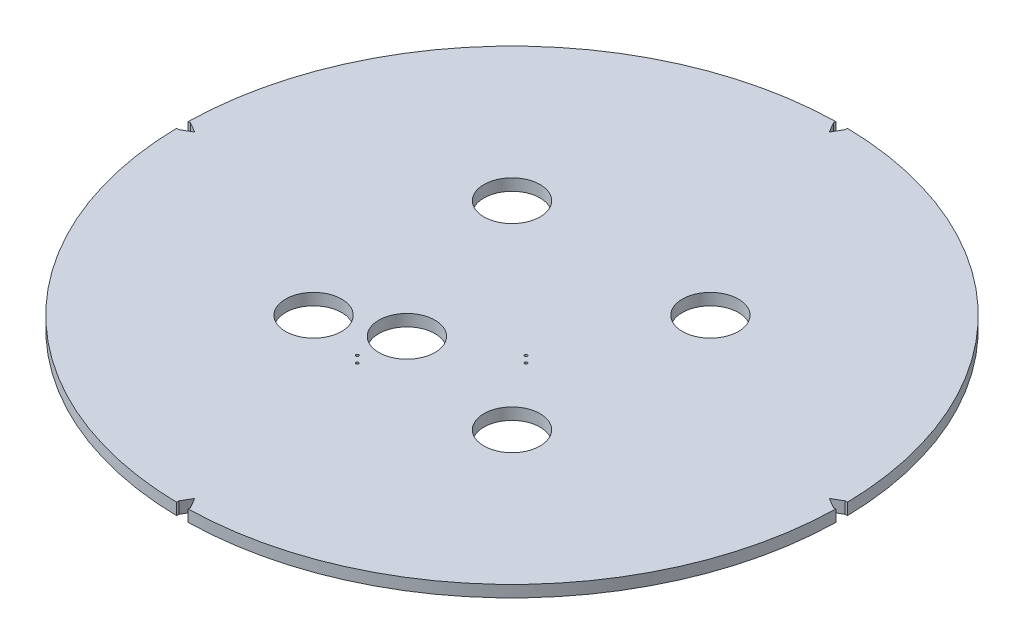
SolidWorks part; units mm, degrees
ref_plane "前视基准面" through (0, 0, 0) normal (0, 0, 1) x (1, 0, 0)
ref_plane "上视基准面" through (0, 0, 0) normal (0, 1, 0) x (1, 0, 0)
ref_plane "右视基准面" through (0, 0, 0) normal (1, 0, 0) x (0, 0, -1)
sketch "草图1" plane through (0, 0, 0) normal (0, 1, 0) x (1, 0, 0)
  circle A0 centre (0, 0) radius 705
  dimension "D1" = 1410
extrude "凸台-拉伸1" add sketch "草图1" along normal blind 25
sketch "草图2" plane through (0, 25, 0) normal (0, 1, 0) x (1, 0, 0)
  line L0 (-12.5, -699.9942) -> (-12.5, -1517.4112) construction
  line L1 (0, -678.3436) -> (-12.5, -699.9942) construction
  line L2 (12.5, -699.9942) -> (0, -678.3436) construction
  line L3 (12.5, -699.9942) -> (12.5, -1517.4112) construction
  line L4 (-12.5, -699.9942) -> (-12.5, -704.8892)
  line L5 (0, -678.3436) -> (-12.5, -699.9942)
  line L6 (12.5, -699.9942) -> (0, -678.3436)
  line L7 (12.5, -699.9942) -> (12.5, -704.8892)
  arc A0 (12.5, -704.8892) -> (-12.5, -704.8892) centre (0, 0) cw
  dimension "D1" = 705
extrude "切除-拉伸1" cut sketch "草图2" against normal up to next
pattern_circular "阵列(圆周)1" count 4 over 360 about axis through (0, 0, 0) along (0, 1, 0) of "切除-拉伸1"
sketch "草图7" plane through (0, 25, 0) normal (0, 1, 0) x (1, 0, 0)
  line L0 (0, 695) -> (0, -695) construction
  line L1 (326.2868, -609.1295) -> (206.0786, -488.9214)
  line L2 (326.2868, -609.1295) -> (467.7082, -467.7082)
  line L3 (467.7082, -467.7082) -> (347.5, -347.5)
  line L4 (206.0786, -488.9214) -> (347.5, -347.5)
  line L5 (326.2868, -609.1295) -> (347.5, -347.5) construction
  line L6 (467.7082, -467.7082) -> (206.0786, -488.9214) construction
  line L7 (-695, 0) -> (695, 0) construction
  line L8 (695, 0) -> (0, -695) construction
  line L9 (491.4392, -491.4392) -> (-491.4392, 491.4392) construction
  line L10 (-612.9008, -323.662) -> (-492.6926, -203.4538)
  line L11 (-612.9008, -323.662) -> (-471.4794, -465.0833)
  line L12 (-471.4794, -465.0833) -> (-351.2713, -344.8752)
  line L13 (-492.6926, -203.4538) -> (-351.2713, -344.8752)
  line L14 (-612.9008, -323.662) -> (-351.2713, -344.8752) construction
  line L15 (-471.4794, -465.0833) -> (-492.6926, -203.4538) construction
  line L16 (-332.2351, 613.6048) -> (-212.027, 493.3967)
  line L17 (-332.2351, 613.6048) -> (-473.6565, 472.1835)
  line L18 (-473.6565, 472.1835) -> (-353.4483, 351.9753)
  line L19 (-212.027, 493.3967) -> (-353.4483, 351.9753)
  line L20 (-332.2351, 613.6048) -> (-353.4483, 351.9753) construction
  line L21 (-473.6565, 472.1835) -> (-212.027, 493.3967) construction
  line L22 (605.0317, 332.9392) -> (484.8235, 212.731)
  line L23 (605.0317, 332.9392) -> (463.6103, 474.3606)
  line L24 (463.6103, 474.3606) -> (343.4022, 354.1524)
  line L25 (484.8235, 212.731) -> (343.4022, 354.1524)
  line L26 (605.0317, 332.9392) -> (343.4022, 354.1524) construction
  line L27 (463.6103, 474.3606) -> (484.8235, 212.731) construction
  line L28 (347.5, -347.5) -> (347.5, 0) construction
  circle A0 centre (0, 0) radius 695
  arc A1 (467.7082, -467.7082) -> (347.5, -347.5) centre (407.6041, -407.6041) ccw
  arc A2 (-471.4794, -465.0833) -> (-351.2713, -344.8752) centre (-411.3753, -404.9792) ccw
  arc A3 (-473.6565, 472.1835) -> (-353.4483, 351.9753) centre (-413.5524, 412.0794) ccw
  arc A4 (463.6103, 474.3606) -> (343.4022, 354.1524) centre (403.5062, 414.2565) ccw
  point P2 (336.8934, -478.3148)
  point P14 (-482.086, -334.2686)
  point P20 (-342.8417, 482.7901)
  point P26 (474.2169, 343.5458)
  point P35 (20.5792, -31.4481)
  dimension "D1" = 1390
  dimension "D2" = 200
  dimension "D3" = 170
sketch "草图8" plane through (0, 25, 0) normal (0, 1, 0) x (1, 0, 0)
  line L0 (491.4392, -491.4392) -> (-491.4392, 491.4392) construction
  circle A0 centre (212.132, -212.132) radius 60
  circle A1 centre (-212.132, -212.132) radius 60
  circle A2 centre (-212.132, 212.132) radius 60
  circle A3 centre (212.132, 212.132) radius 60
  point P13 (0, 0)
  dimension "D3" = 120
  dimension "D2" = 300
  dimension "D1" = 4
extrude "切除-拉伸2" cut sketch "草图8" against normal up to next
sketch "草图9" plane through (0, 25, 0) normal (0, 1, 0) x (1, 0, 0)
  line L0 (-82.9781, -126.8961) -> (-50.0682, -138.8099) construction
  line L1 (-82.9781, -126.8961) -> (-50.0682, -138.8099)
sketch "草图10" plane through (0, 25, 0) normal (0, 1, 0) x (1, 0, 0)
  line L0 (-82.9781, -126.8961) -> (-50.0682, -138.8099) construction
  line L1 (-82.9781, -126.8961) -> (-50.0682, -138.8099)
  line L2 (-50.0682, -138.8099) -> (-58.576, -162.3114)
  line L3 (-58.576, -162.3114) -> (-91.4859, -150.3976)
  line L4 (-91.4859, -150.3976) -> (-82.9781, -126.8961)
sketch "草图11" plane through (0, 25, 0) normal (0, 1, 0) x (1, 0, 0)
  line L1 (-36.1645, -101.1698) -> (-68.9964, -89.0426) construction
  line L2 (-73.37, -151.3894) -> (-52.5805, -95.1062) construction
  circle A0 centre (-73.37, -151.3894) radius 60
extrude "切除-拉伸3" cut sketch "草图11" against normal blind 100
sketch "草图12" plane through (0, 0, 0) normal (0, -1, 0) x (1, 0, 0)
  line L0 (-73.37, 151.3894) -> (-30.9436, 193.8158)
  line L1 (491.4392, 491.4392) -> (-491.4392, -491.4392) construction
  line L2 (-30.9436, 193.8158) -> (96.3356, 66.5366)
  line L3 (89.2646, 59.4655) -> (103.4067, 73.6076)
  line L4 (-165.2939, 314.0239) -> (-163.1725, 316.1453)
  line L5 (-30.9436, 193.8158) -> (-83.9766, 246.8488)
  line L6 (-83.9766, 246.8488) -> (-91.0477, 239.7777)
  circle A0 centre (-73.37, 151.3894) radius 60 construction
  circle A1 centre (103.4067, 73.6076) radius 3
  circle A2 centre (89.2646, 59.4655) radius 3
  circle A3 centre (-91.0477, 239.7777) radius 3
  circle A4 centre (-76.9055, 253.9199) radius 3
  dimension "D1" = 180
  dimension "D2" = 75
extrude "切除-拉伸4" cut sketch "草图12" against normal through all
sketch "草图13" plane through (0, 0, 0) normal (0, -1, 0) x (1, 0, 0)
  line L0 (-30.9436, 193.8158) -> (-83.9766, 246.8488) construction
  line L1 (491.4392, 491.4392) -> (-491.4392, -491.4392) construction
  line L2 (-83.9766, 246.8488) -> (-76.9055, 253.9199) construction
  circle A1 centre (-73.37, 151.3894) radius 60 construction
  circle A2 centre (-76.9055, 253.9199) radius 3
  circle A3 centre (-91.0477, 239.7777) radius 3
extrude "切除-拉伸5" cut sketch "草图13" against normal blind 30 contours A3 | A2
